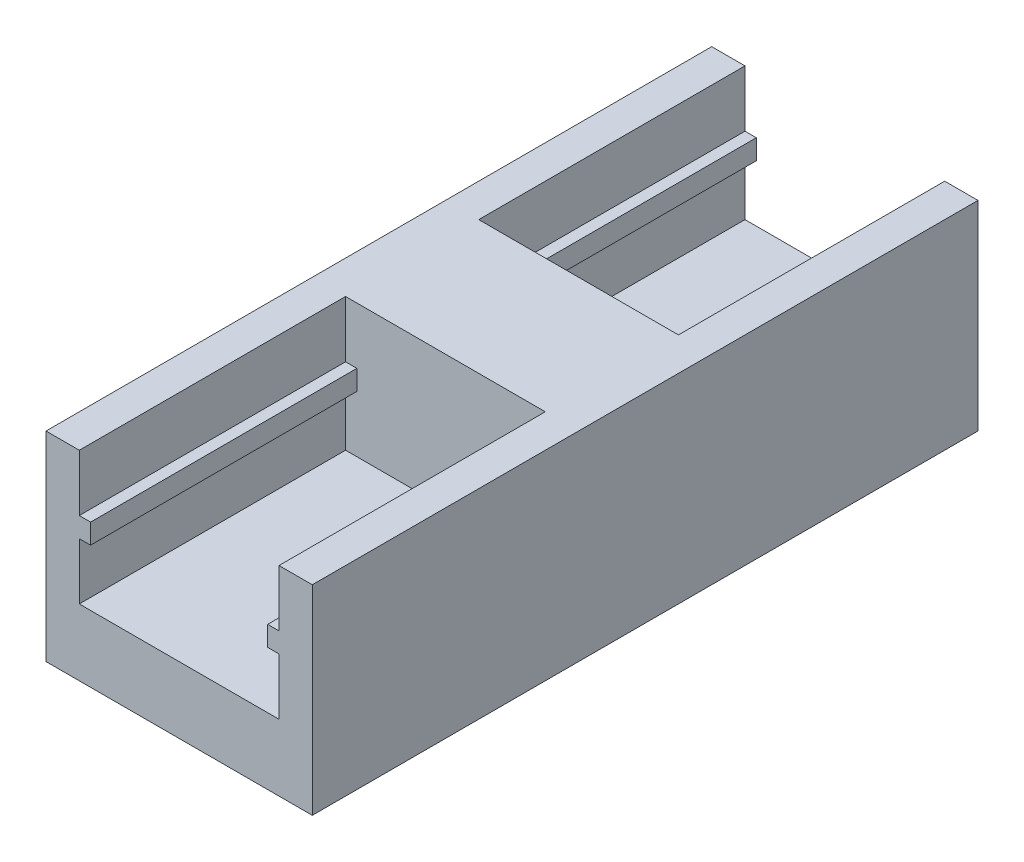
SolidWorks part; units mm, degrees
ref_plane "Front Plane" through (0, 0, 0) normal (0, 0, 1) x (1, 0, 0)
ref_plane "Top Plane" through (0, 0, 0) normal (0, 1, 0) x (1, 0, 0)
ref_plane "Right Plane" through (0, 0, 0) normal (1, 0, 0) x (0, 0, -1)
sketch "Sketch2" plane through (0, 0, 0) normal (0, 0, 1) x (1, 0, 0)
  line L1 (-10, -7.5) -> (10, -7.5)
  line L2 (-10, -7.5) -> (-10, 7.5)
  line L3 (-10, 7.5) -> (10, 7.5)
  line L4 (10, -7.5) -> (10, 7.5)
  line L5 (-10, -7.5) -> (10, 7.5) construction
  line L6 (-10, 7.5) -> (10, -7.5) construction
  point P0 (0, 0)
  dimension "D1" = 20
  dimension "D2" = 15
extrude "Boss-Extrude1" add sketch "Sketch2" along normal blind 50
sketch "Sketch4" plane through (0, 0, 50) normal (0, 0, 1) x (1, 0, 0)
  line L0 (0, 7.5) -> (0, -7.5) construction
  line L1 (10, 7.5) -> (-10, 7.5) construction
  line L2 (-10, -7.5) -> (10, -7.5) construction
  line L3 (-6.65, 2.5) -> (6.65, 2.5) construction
  line L4 (-7.5, -2.5) -> (7.5, -2.5)
  line L5 (-7.5, -2.5) -> (-7.5, 1.75)
  line L6 (-7.5, 7.5) -> (7.5, 7.5)
  line L7 (7.5, -2.5) -> (7.5, 1.75)
  line L8 (-7.5, -2.5) -> (7.5, 7.5) construction
  line L9 (-7.5, 7.5) -> (7.5, -2.5) construction
  line L10 (-6.65, 1.75) -> (-6.65, 3.25)
  line L11 (-6.65, 3.25) -> (-7.5, 3.25)
  line L12 (-6.65, 1.75) -> (-7.5, 1.75)
  line L13 (-7.5, 3.25) -> (-7.5, 7.5)
  line L14 (6.65, 1.75) -> (6.65, 3.25)
  line L15 (6.65, 1.75) -> (7.5, 1.75)
  line L16 (6.65, 3.25) -> (7.5, 3.25)
  line L17 (7.5, 3.25) -> (7.5, 7.5)
  point P6 (0, 2.5)
  point P12 (0, 7.5)
  point P13 (0, 0)
  point P16 (-6.65, 2.5)
  dimension "D1" = 15
  dimension "D2" = 10
  dimension "D3" = 1.5
  dimension "D4" = 0.85
extrude "Cut-Extrude2" cut sketch "Sketch4" against normal blind 20
sketch "Sketch5" plane through (0, 7.5, 0) normal (0, 1, 0) x (1, 0, 0)
  line L0 (-10, -25) -> (10, -25) construction
  line L1 (-10, -50) -> (-10, 0) construction
  line L2 (10, -50) -> (10, 0) construction
ref_plane "Plane4" through (0, 0, 25) normal (0, 0, 1) x (1, 0, 0)
mirror "Mirror1" about plane through (0, 0, 25) normal (0, 0, 1) of "Cut-Extrude2"
